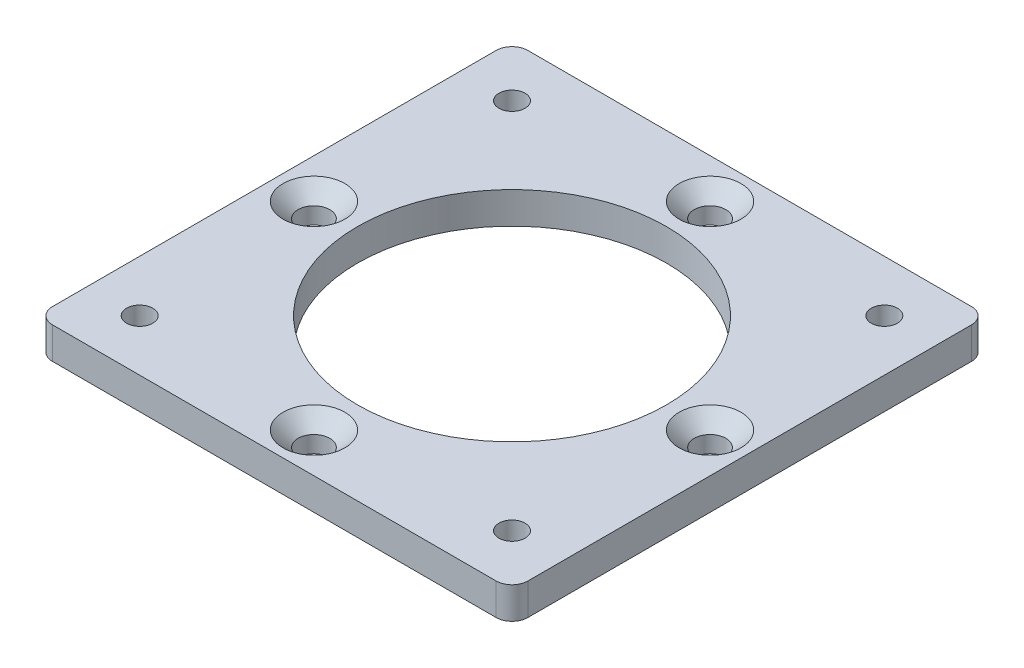
SolidWorks part; units mm, degrees
ref_plane "Спереди" through (0, 0, 0) normal (0, 0, 1) x (1, 0, 0)
ref_plane "Сверху" through (0, 0, 0) normal (0, 1, 0) x (1, 0, 0)
ref_plane "Справа" through (0, 0, 0) normal (1, 0, 0) x (0, 0, -1)
sketch "Эскиз1" plane through (0, 0, 0) normal (0, 1, 0) x (1, 0, 0)
  line L0 (-9.0949, 33.781) -> (-9.0949, -26.219) construction
  line L1 (-39.0949, 33.781) -> (20.9051, 33.781)
  line L2 (-39.0949, 33.781) -> (-39.0949, -26.219)
  line L3 (-39.0949, -26.219) -> (20.9051, -26.219)
  line L4 (20.9051, 33.781) -> (20.9051, -26.219)
  line L5 (-9.0949, -26.219) -> (20.9051, 3.781) construction
  line L6 (20.9051, 3.781) -> (-39.0949, 3.781) construction
  line L7 (-32.5949, 27.281) -> (14.4051, 27.281) construction
  line L8 (14.4051, 27.281) -> (14.4051, -19.719) construction
  line L9 (14.4051, -19.719) -> (-32.5949, -19.719) construction
  line L10 (-32.5949, -19.719) -> (-32.5949, 27.281) construction
  circle A0 centre (-32.5949, 27.281) radius 1.65
  circle A1 centre (14.4051, 27.281) radius 1.65
  circle A2 centre (-32.5949, -19.719) radius 1.65
  circle A3 centre (14.4051, -19.719) radius 1.65
  circle A4 centre (-9.0949, 3.781) radius 19.5
  circle A5 centre (-34.0949, 3.781) radius 2
  circle A6 centre (15.9051, 3.781) radius 2
  circle A7 centre (-9.0949, 3.781) radius 25 construction
  circle A8 centre (-9.0949, 28.781) radius 2
  circle A9 centre (-9.0949, -21.219) radius 2
  dimension "D3" = 23.5
  dimension "D4" = 47
  dimension "D7" = 3.3
  dimension "D8" = 3.3
  dimension "D9" = 3.3
  dimension "D10" = 3.3
  dimension "D11" = 39
  dimension "D12" = 4
  dimension "D13" = 4
  dimension "D14" = 50
  dimension "D16" = 4
  dimension "D17" = 4
  dimension "D1" = 60
  dimension "D2" = 60
  dimension "D5" = 23.5
  dimension "D6" = 23.5
  dimension "D15" = 25
extrude "Бобышка-Вытянуть1" add sketch "Эскиз1" along normal blind 4
fillet "Скругление1" radius 2 4 edges at (-39.0949, 2, -33.781) (20.9051, 2, -33.781) (20.9051, 2, 26.219) (-39.0949, 2, 26.219)
chamfer "Фаска1" distance 1.9 angle 45 4 edges at (-34.0949, 4, -1.781) (15.9051, 4, -1.781) (-9.0949, 4, 23.219) (-9.0949, 4, -26.781)
